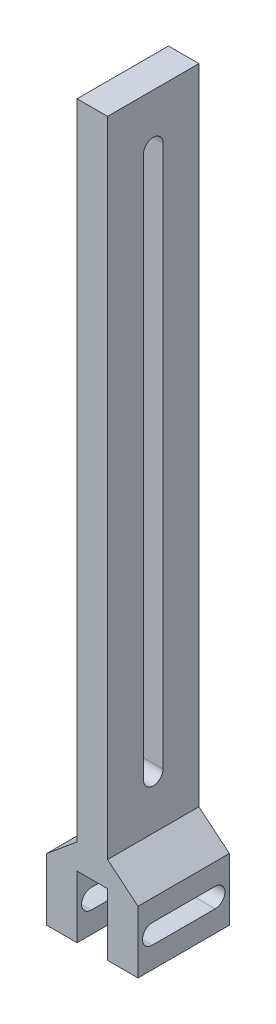
SolidWorks part; units mm, degrees
ref_plane "Plan de face" through (0, 0, 0) normal (0, 0, 1) x (1, 0, 0)
ref_plane "Plan de dessus" through (0, 0, 0) normal (0, 1, 0) x (1, 0, 0)
ref_plane "Plan de droite" through (0, 0, 0) normal (1, 0, 0) x (0, 0, -1)
sketch "Esquisse1" plane through (0, 0, 0) normal (0, 0, 1) x (1, 0, 0)
  line L0 (-7.5, 0) -> (-2.5, 0)
  line L1 (0, -55) -> (0, 55) construction
  line L2 (7.5, 0) -> (2.5, 0)
  line L3 (-2.5, 0) -> (-2.5, 10.2)
  line L4 (-2.5, 10.2) -> (2.5, 10.2)
  line L5 (2.5, 10.2) -> (2.5, 0)
  line L6 (-7.5, 0) -> (-7.5, 10.2)
  line L7 (-7.5, 10.2) -> (-2.5, 14.3419)
  line L8 (-2.5, 14.3419) -> (-2.5, 120)
  line L9 (-2.5, 120) -> (2.5, 120)
  line L10 (2.5, 120) -> (2.5, 14.3419)
  line L11 (2.5, 14.3419) -> (7.5, 10.2)
  line L12 (7.5, 10.2) -> (7.5, 0)
  dimension "D1" = 5
  dimension "D2" = 2.5
  dimension "D3" = 10.2
  dimension "D4" = 120
extrude "Boss.-Extru.1" add sketch "Esquisse1" along normal mid plane 15
sketch "Esquisse2" plane through (-7.5, 0, 0) normal (-1, 0, 0) x (0, 0, 1)
  line L0 (-7.5, 5.1) -> (7.5, 5.1) construction
  line L1 (-7.5, 10.2) -> (-7.5, 0) construction
  line L2 (7.5, 10.2) -> (7.5, 0) construction
  line L3 (-5.1643, 5.1) -> (5.1643, 5.1) construction
  line L4 (-5.1643, 6.7) -> (5.1643, 6.7)
  line L5 (-5.1643, 3.5) -> (5.1643, 3.5)
  arc A0 (-5.1643, 6.7) -> (-5.1643, 3.5) centre (-5.1643, 5.1) ccw
  arc A1 (5.1643, 3.5) -> (5.1643, 6.7) centre (5.1643, 5.1) ccw
  point P8 (0, 5.1)
  dimension "D1" = 3.2
extrude "Enlèv. mat.-Extru.1" cut sketch "Esquisse2" against normal blind 25
sketch "Esquisse3" plane through (-2.5, 0, 0) normal (-1, 0, 0) x (0, 0, 1)
  line L0 (0, 120) -> (0, 14.3419) construction
  line L1 (7.5, 120) -> (-7.5, 120) construction
  line L2 (7.5, 14.3419) -> (-7.5, 14.3419) construction
  line L3 (0, 22.674) -> (0, 111.6679) construction
  line L4 (-1.6, 22.674) -> (-1.6, 111.6679)
  line L5 (1.6, 22.674) -> (1.6, 111.6679)
  arc A0 (-1.6, 22.674) -> (1.6, 22.674) centre (0, 22.674) ccw
  arc A1 (1.6, 111.6679) -> (-1.6, 111.6679) centre (0, 111.6679) ccw
  point P8 (0, 67.1709)
  dimension "D1" = 3.2
extrude "Enlèv. mat.-Extru.2" cut sketch "Esquisse3" against normal blind 25
